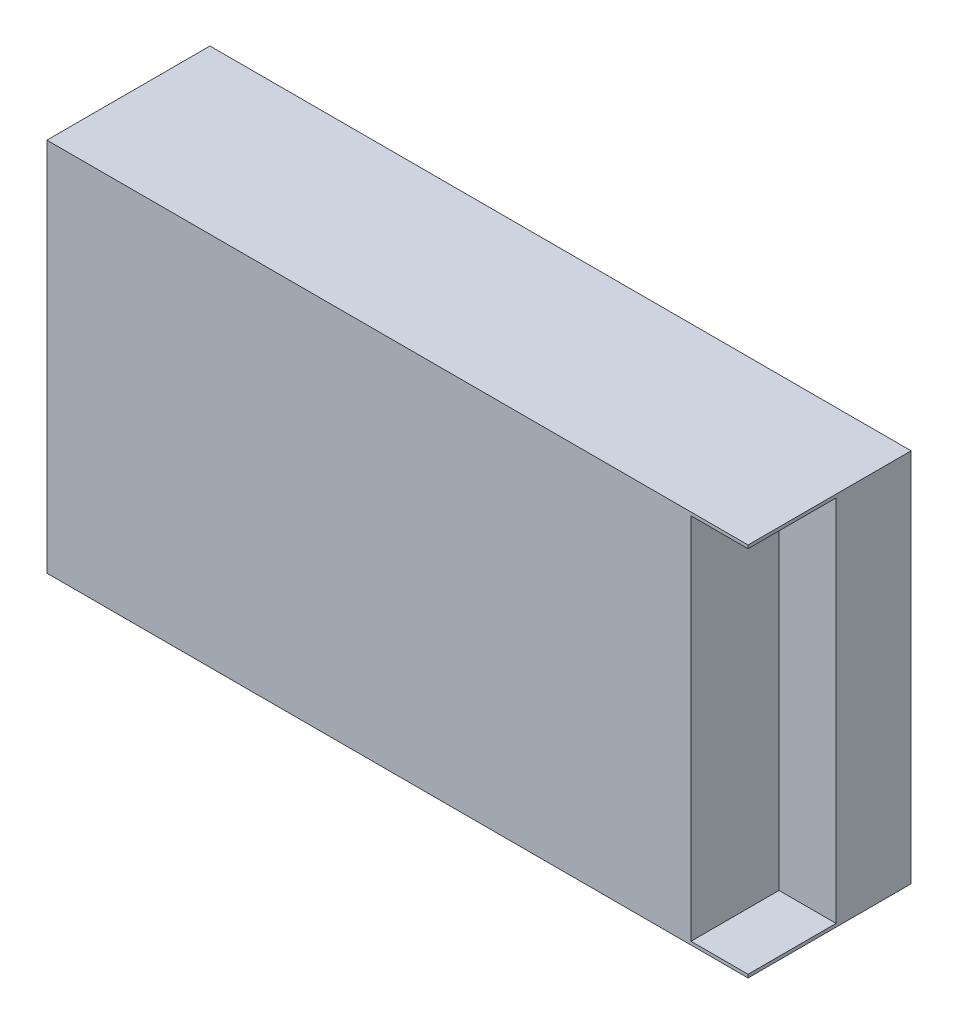
SolidWorks part; units mm, degrees
ref_plane "Front Plane" through (0, 0, 0) normal (0, 0, 1) x (1, 0, 0)
ref_plane "Top Plane" through (0, 0, 0) normal (0, 1, 0) x (1, 0, 0)
ref_plane "Right Plane" through (0, 0, 0) normal (1, 0, 0) x (0, 0, -1)
sketch "Sketch1" plane through (0, 0, 0) normal (0, 0, 1) x (1, 0, 0)
  line L1 (0, 0) -> (215, 0)
  line L2 (0, 0) -> (0, 115)
  line L3 (0, 115) -> (215, 115)
  line L4 (215, 0) -> (215, 115)
  dimension "D1" = 215
  dimension "D2" = 115
extrude "Boss-Extrude1" add sketch "Sketch1" along normal blind 50
sketch "Sketch2" plane through (0, 0, 50) normal (0, 0, 1) x (1, 0, 0)
  line L1 (215, 114) -> (197.5, 114)
  line L2 (215, 114) -> (215, 1)
  line L3 (215, 1) -> (197.5, 1)
  line L4 (197.5, 114) -> (197.5, 1)
  line L6 (0, 0) -> (215, 0) construction
  line L7 (215, 115) -> (0, 115) construction
  line L8 (215, 0) -> (215, 115) construction
  dimension "D1" = 17.5
  dimension "D2" = 1
  dimension "D3" = 1
extrude "Cut-Extrude1" cut sketch "Sketch2" against normal blind 27
